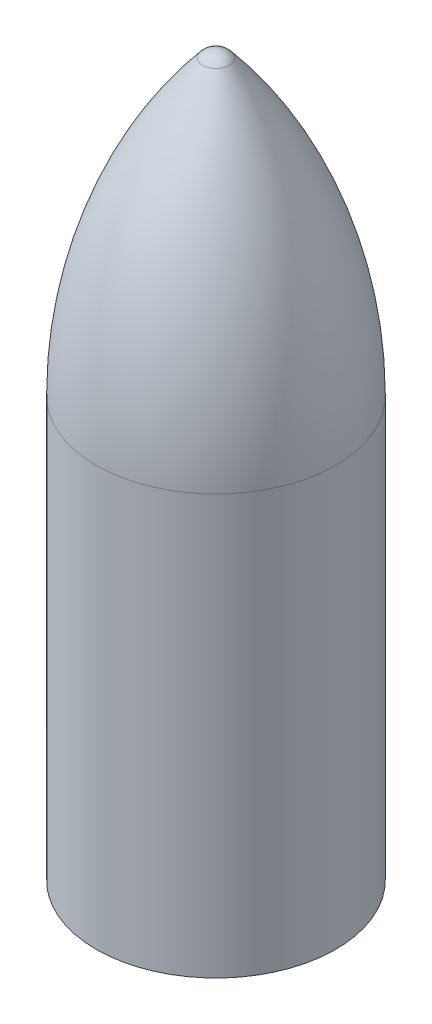
SolidWorks part; units mm, degrees
ref_plane "Front Plane" through (0, 0, 0) normal (0, 0, 1) x (1, 0, 0)
ref_plane "Top Plane" through (0, 0, 0) normal (0, 1, 0) x (1, 0, 0)
ref_plane "Right Plane" through (0, 0, 0) normal (1, 0, 0) x (0, 0, -1)
sketch "Sketch1" plane through (0, 0, 0) normal (0, 0, 1) x (1, 0, 0)
  line L0 (0, 255.4558) -> (0, -224.3926) construction
  line L1 (-50.8, 0) -> (-50.8, 177.8)
  line L2 (-50.8, 0) -> (0, 0)
  line L3 (0, 304.8) -> (0, 0)
  arc A0 (-50.8, 177.8) -> (-5.6696, 302.1499) centre (143.0786, 177.8) cw
  arc A1 (-5.6696, 302.1499) -> (0, 304.8) centre (0, 297.4103) cw
  dimension "D1" = 304.8
  dimension "D2" = 50.8
  dimension "D3" = 177.8
revolve "Revolve1" add sketch "Sketch1" angle 360 about L0
shell "Shell1" thickness 2.54
